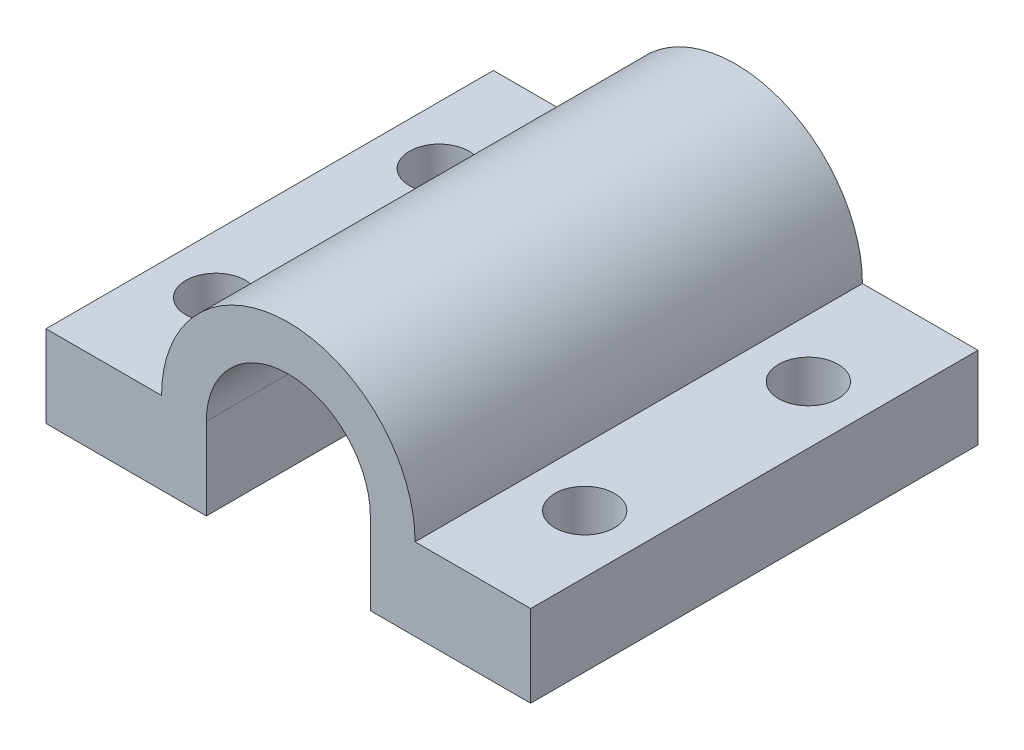
SolidWorks part; units mm, degrees
ref_plane "Front Plane" through (0, 0, 0) normal (0, 0, 1) x (1, 0, 0)
ref_plane "Top Plane" through (0, 0, 0) normal (0, 1, 0) x (1, 0, 0)
ref_plane "Right Plane" through (0, 0, 0) normal (1, 0, 0) x (0, 0, -1)
sketch "Sketch1" plane through (0, 0, 0) normal (0, 0, 1) x (1, 0, 0)
  line L0 (0, 74.9717) -> (0, -73.1564) construction
  line L1 (-108.7362, 0) -> (119.628, 0) construction
  line L2 (-2.2, 0) -> (-2.2, -2.2)
  line L3 (-2.2, -2.2) -> (-6.5, -2.2)
  line L4 (-6.5, -2.2) -> (-6.5, 0)
  line L5 (-6.5, 0) -> (-3.4, 0)
  line L6 (2.2, 0) -> (2.2, -2.2)
  line L7 (2.2, -2.2) -> (6.5, -2.2)
  line L8 (6.5, -2.2) -> (6.5, 0)
  line L9 (6.5, 0) -> (3.4, 0)
  arc A0 (-2.2, 0) -> (2.2, 0) centre (0, 0) cw
  arc A1 (-3.4, 0) -> (3.4, 0) centre (0, 0) cw
  dimension "D1" = 3.4
  dimension "D2" = 2.2
  dimension "D3" = 2.2
  dimension "D4" = 6.5
  dimension "D5" = 3.1
extrude "Boss-Extrude1" add sketch "Sketch1" along normal blind 12
sketch "Sketch2" plane through (0, 0, 0) normal (0, 1, 0) x (1, 0, 0)
  line L0 (-4.95, 0) -> (-4.95, -12) construction
  line L1 (-3.4, 0) -> (-6.5, 0) construction
  line L2 (-3.4, -12) -> (-6.5, -12) construction
  line L3 (0, 0) -> (0, -12) construction
  line L4 (-3.4, -12) -> (3.4, -12) construction
  line L5 (-4.95, -6) -> (6.5, -6) construction
  line L6 (6.5, -12) -> (6.5, 0) construction
  circle A0 centre (-4.95, -3) radius 0.8
  circle A1 centre (-4.95, -9) radius 0.8
  circle A2 centre (4.95, -3) radius 0.8
  circle A3 centre (4.95, -9) radius 0.8
  point P8 (-4.95, -6)
  dimension "D1" = 3
  dimension "D2" = 4.95
extrude "Cut-Extrude1" cut sketch "Sketch2" against normal blind 20
